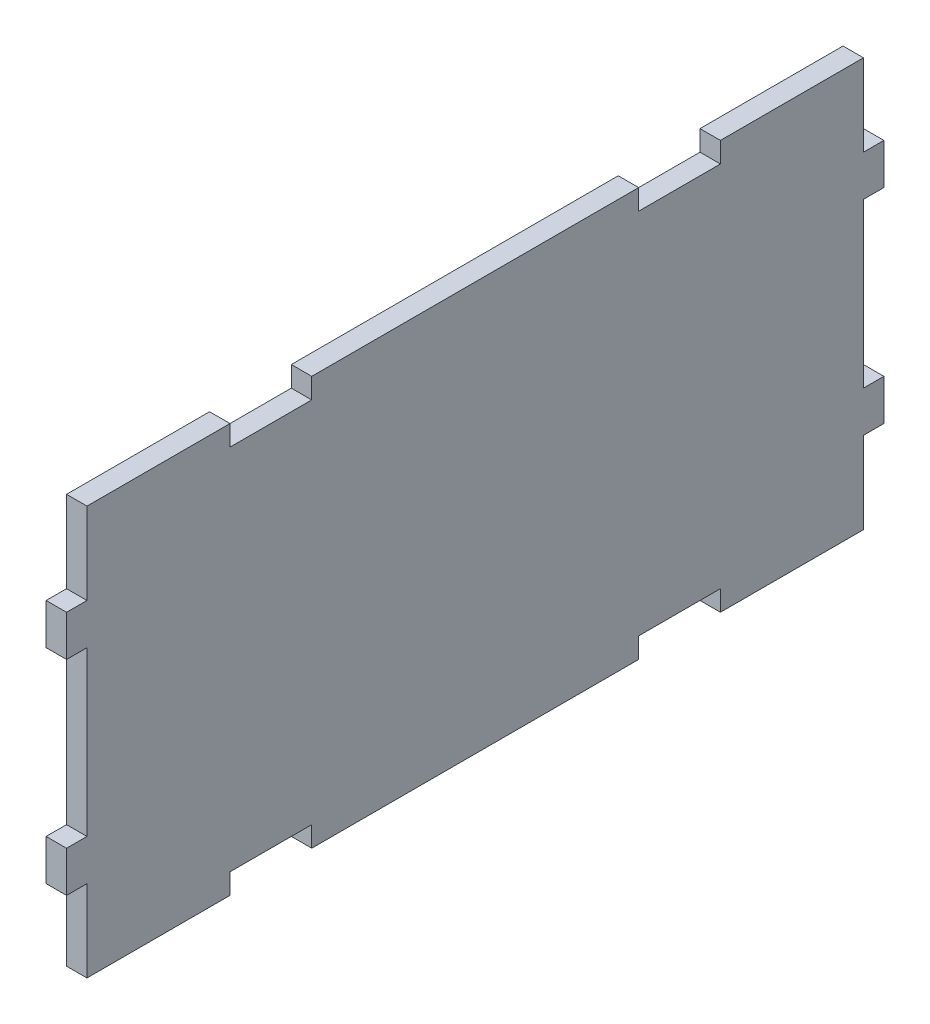
SolidWorks part; units mm, degrees
ref_plane "Front Plane" through (0, 0, 0) normal (0, 0, 1) x (1, 0, 0)
ref_plane "Top Plane" through (0, 0, 0) normal (0, 1, 0) x (1, 0, 0)
ref_plane "Right Plane" through (0, 0, 0) normal (1, 0, 0) x (0, 0, -1)
sketch "Sketch1" plane through (0, 0, 0) normal (1, 0, 0) x (0, 0, -1)
  line L0 (-76.1508, -61.6178) -> (-41.1508, -61.6178)
  line L1 (-76.1508, 38.3822) -> (-41.1508, 38.3822)
  line L2 (-81.1508, 18.3822) -> (-81.1508, 8.3822)
  line L3 (58.8492, -61.6178) -> (58.8492, -56.6178)
  line L4 (113.8492, 38.3822) -> (113.8492, 18.3822)
  line L5 (-41.1508, -61.6178) -> (-41.1508, -56.6178)
  line L6 (-41.1508, -56.6178) -> (-21.1508, -56.6178)
  line L7 (-21.1508, -56.6178) -> (-21.1508, -61.6178)
  line L8 (-21.1508, -61.6178) -> (58.8492, -61.6178)
  line L9 (58.8492, -56.6178) -> (78.8492, -56.6178)
  line L10 (78.8492, -61.6178) -> (113.8492, -61.6178)
  line L11 (78.8492, -61.6178) -> (78.8492, -56.6178)
  line L12 (-21.1508, 38.3822) -> (58.8492, 38.3822)
  line L13 (58.8492, 33.3822) -> (78.8492, 33.3822)
  line L14 (113.8492, 18.3822) -> (118.8492, 18.3822)
  line L15 (-41.1508, 33.3822) -> (-21.1508, 33.3822)
  line L16 (-76.1508, 38.3822) -> (-76.1508, 18.3822)
  line L17 (-41.1508, 33.3822) -> (-41.1508, 38.3822)
  line L18 (-76.1508, 18.3822) -> (-81.1508, 18.3822)
  line L19 (-21.1508, 33.3822) -> (-21.1508, 38.3822)
  line L20 (-21.1508, 38.3822) -> (58.8492, 38.3822)
  line L21 (58.8492, 38.3822) -> (58.8492, 33.3822)
  line L22 (58.8492, 33.3822) -> (78.8492, 33.3822)
  line L23 (78.8492, 33.3822) -> (78.8492, 38.3822)
  line L24 (-81.1508, 8.3822) -> (-76.1508, 8.3822)
  line L25 (-76.1508, 8.3822) -> (-76.1508, -31.6178)
  line L26 (-76.1508, -31.6178) -> (-81.1508, -31.6178)
  line L27 (-81.1508, -31.6178) -> (-81.1508, -41.6178)
  line L28 (-81.1508, -41.6178) -> (-76.1508, -41.6178)
  line L29 (-76.1508, -41.6178) -> (-76.1508, -61.6178)
  line L30 (78.8492, 38.3822) -> (113.8492, 38.3822)
  line L31 (118.8492, 18.3822) -> (118.8492, 8.3822)
  line L32 (118.8492, 8.3822) -> (113.8492, 8.3822)
  line L33 (113.8492, 8.3822) -> (113.8492, -31.6178)
  line L34 (113.8492, -31.6178) -> (118.8492, -31.6178)
  line L35 (118.8492, -31.6178) -> (118.8492, -41.6178)
  line L36 (118.8492, -41.6178) -> (113.8492, -41.6178)
  line L37 (113.8492, -41.6178) -> (113.8492, -61.6178)
  dimension "D1" = 200
  dimension "D2" = 5
  dimension "D3" = 35
  dimension "D4" = 20
  dimension "D5" = 80
  dimension "D6" = 20
  dimension "D7" = 35
  dimension "D8" = 5
  dimension "D9" = 100
  dimension "D10" = 40
  dimension "D11" = 10
  dimension "D12" = 20
  dimension "D13" = 20
  dimension "D14" = 10
extrude "Boss-Extrude1" add sketch "Sketch1" along normal blind 5 contours L37 L36 L35 L34 L33 L32 L31 L14 L4 L30 L23 L13 L21 L12 L19 L15 L17 L1 L16 L18 L2 L24 L25 L26 L27 L28 L29 L0 L5 L6 L7 L8 L3 L9 L11 L10
